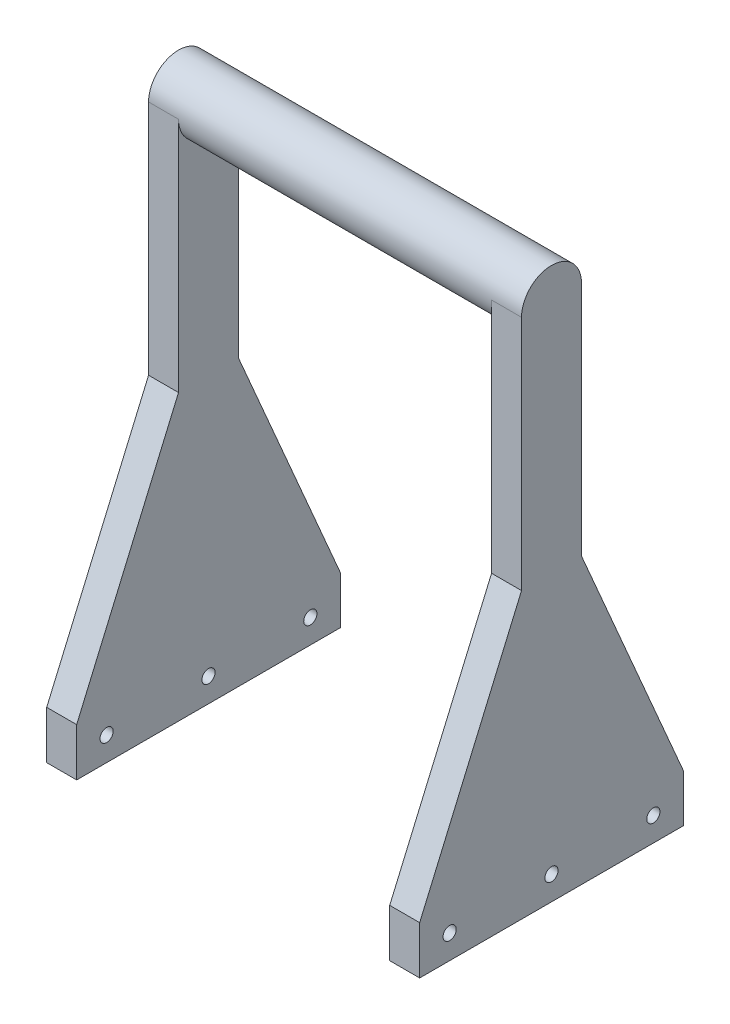
SolidWorks part; units mm, degrees
ref_plane "前视基准面" through (0, 0, 0) normal (0, 0, 1) x (1, 0, 0)
ref_plane "上视基准面" through (0, 0, 0) normal (0, 1, 0) x (1, 0, 0)
ref_plane "右视基准面" through (0, 0, 0) normal (1, 0, 0) x (0, 0, -1)
sketch "草图2" plane through (0, 0, 0) normal (0, 1, 0) x (1, 0, 0)
  line L0 (0, 27.4644) -> (0, -23.7489) construction
  line L1 (-36.2271, 0) -> (41.5528, 0) construction
  line L3 (-62.25, 44) -> (-52.25, 44)
  line L4 (-62.25, 44) -> (-62.25, -44)
  line L5 (-62.25, -44) -> (-52.25, -44)
  line L6 (-52.25, 44) -> (-52.25, -44)
  line L7 (-62.25, 44) -> (-52.25, -44) construction
  line L8 (-62.25, -44) -> (-52.25, 44) construction
  line L9 (52.25, 44) -> (62.25, 44)
  line L10 (52.25, 44) -> (52.25, -44)
  line L11 (52.25, -44) -> (62.25, -44)
  line L12 (62.25, 44) -> (62.25, -44)
  line L13 (52.25, 44) -> (62.25, -44) construction
  line L14 (52.25, -44) -> (62.25, 44) construction
  point P5 (-57.25, 0)
  point P10 (57.25, 0)
  dimension "D1" = 52.25
  dimension "D2" = 52.25
  dimension "D3" = 10
  dimension "D4" = 10
  dimension "D5" = 88
  dimension "D6" = 88
extrude "凸台-拉伸1" add sketch "草图2" along normal blind 16
sketch "草图3" plane through (0, 16, 0) normal (0, 1, 0) x (1, 0, 0)
  line L0 (0, 44.2315) -> (0, -45.1645) construction
  line L1 (-40.542, 0) -> (49.5325, 0) construction
  line L2 (-62.25, 44) -> (-62.25, -44) construction
  line L3 (-62.25, 10) -> (-52.25, 10)
  line L4 (-62.25, 10) -> (-62.25, -10)
  line L5 (-62.25, -10) -> (-52.25, -10)
  line L6 (-52.25, 10) -> (-52.25, -10)
  line L7 (-52.25, -44) -> (-52.25, 44) construction
  line L8 (62.25, -10) -> (52.25, -10)
  line L9 (52.25, 10) -> (52.25, -10)
  line L10 (62.25, 10) -> (52.25, 10)
  line L11 (62.25, 10) -> (62.25, -10)
  dimension "D1" = 10
  dimension "D2" = 10
extrude "凸台-拉伸2" add sketch "草图3" along normal blind 158
sketch "草图4" plane through (-62.25, 0, 0) normal (-1, 0, 0) x (0, 0, 1)
  line L0 (-10, 174) -> (10, 174) construction
  circle A0 centre (0, 174) radius 10
extrude "凸台-拉伸3" add sketch "草图4" against normal blind 124.5
sketch "草图5" plane through (-62.25, 0, 0) normal (-1, 0, 0) x (0, 0, 1)
  line L0 (-44, 8) -> (44, 8) construction
  line L1 (-44, 16) -> (-44, 0) construction
  line L2 (44, 16) -> (44, 0) construction
  line L3 (0, 112.2704) -> (0, 0) construction
  circle A0 centre (0, 8) radius 2.2
  circle A1 centre (-34, 8) radius 2.2
  circle A2 centre (34, 8) radius 2.2
  dimension "D1" = 4.4
  dimension "D2" = 4.4
  dimension "D3" = 4.4
  dimension "D4" = 34
  dimension "D5" = 34
extrude "切除-拉伸1" cut sketch "草图5" against normal blind 126
sketch "草图6" plane through (-62.25, 0, 0) normal (-1, 0, 0) x (0, 0, 1)
  line L0 (-44, 16) -> (-10, 95)
  line L1 (-10, 174) -> (-10, 16) construction
  line L6 (0, 0) -> (0, 51.1934) construction
  line L7 (-44, 0) -> (44, 0) construction
  line L8 (44, 16) -> (10, 95)
  line L13 (-10, 95) -> (-10, 16)
  line L14 (-10, 16) -> (-44, 16)
  line L15 (10, 95) -> (10, 16)
  line L16 (10, 16) -> (44, 16)
extrude "凸台-拉伸4" add sketch "草图6" against normal blind 10
sketch "草图7" plane through (62.25, 0, 0) normal (1, 0, 0) x (0, 0, -1)
  line L0 (0, 0) -> (0, 117.2713) construction
  line L1 (-44, 0) -> (44, 0) construction
  line L2 (-44, 16) -> (-10, 95)
  line L3 (-10, 174) -> (-10, 16) construction
  line L9 (44, 16) -> (10, 95)
  line L13 (-10, 95) -> (-10, 16)
  line L14 (-10, 16) -> (-44, 16)
  line L15 (10, 95) -> (10, 16)
  line L16 (10, 174) -> (10, 16) construction
  line L17 (10, 16) -> (44, 16)
extrude "凸台-拉伸5" add sketch "草图7" against normal blind 10
